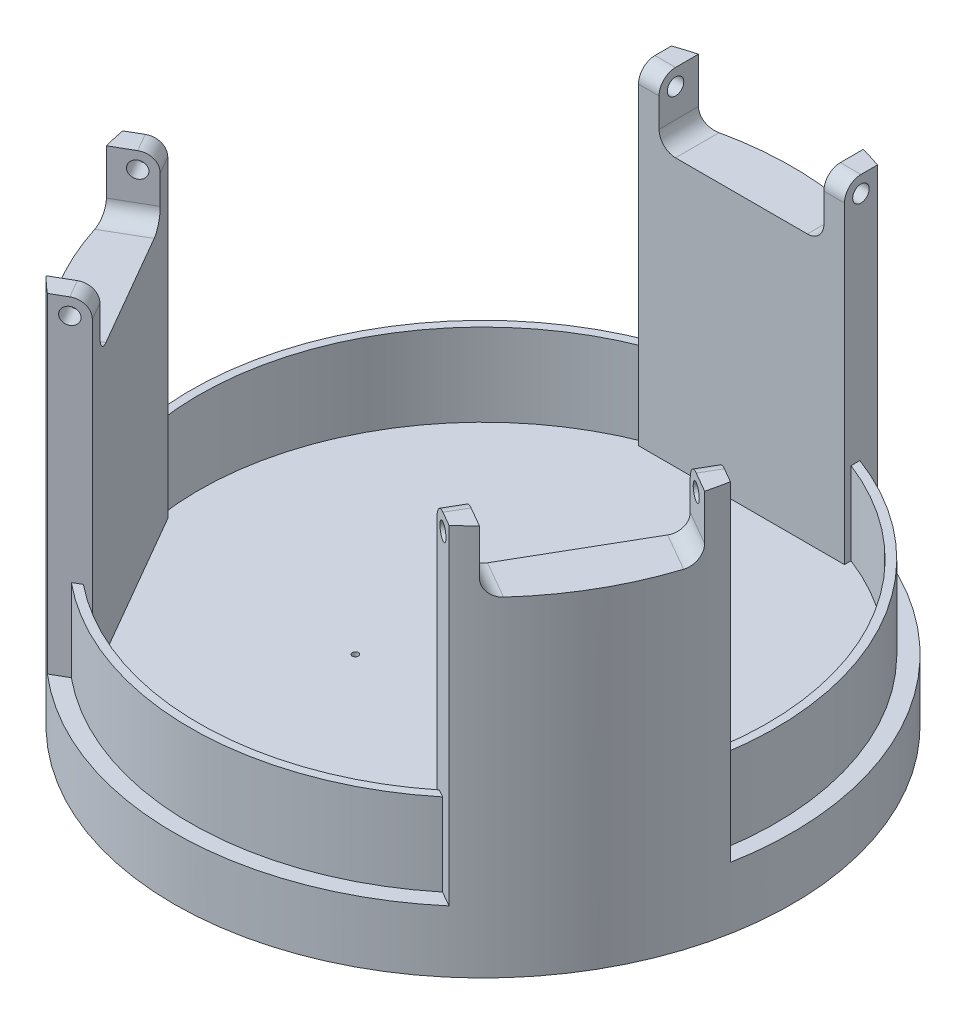
SolidWorks part; units mm, degrees
ref_plane "Front Plane" through (0, 0, 0) normal (0, 0, 1) x (1, 0, 0)
ref_plane "Top Plane" through (0, 0, 0) normal (0, 1, 0) x (1, 0, 0)
ref_plane "Right Plane" through (0, 0, 0) normal (1, 0, 0) x (0, 0, -1)
sketch "Sketch1" plane through (0, 0, 0) normal (0, 1, 0) x (1, 0, 0)
  circle A0 centre (0, 0) radius 75
  dimension "D1" = 150
extrude "Boss-Extrude1" add sketch "Sketch1" along normal blind 15
sketch "Sketch2" plane through (0, 15, 0) normal (0, 1, 0) x (1, 0, 0)
  line L2 (-25, 70.7107) -> (-25, 62.7107)
  line L3 (-25, 62.7107) -> (25, 62.7107)
  line L4 (25, 70.7107) -> (25, 62.7107)
  circle A0 centre (0, 0) radius 75 construction
  arc A1 (-25, 70.7107) -> (25, 70.7107) centre (0, 0) cw
  point P7 (0, 62.7107)
  dimension "D1" = 50
  dimension "D2" = 50
  dimension "D3" = 8
extrude "Boss-Extrude2" add sketch "Sketch2" along normal blind 80
sketch "Sketch3" plane through (0, 95, 0) normal (0, 1, 0) x (1, 0, 0)
  line L0 (-25, 62.7107) -> (25, 62.7107) construction
  line L2 (-20, 72.2842) -> (-20, 62.7107)
  line L3 (-20, 62.7107) -> (20, 62.7107)
  line L4 (20, 72.2842) -> (20, 62.7107)
  arc A0 (25, 70.7107) -> (-25, 70.7107) centre (0, 0) ccw construction
  arc A1 (-20, 72.2842) -> (20, 72.2842) centre (0, 0) cw
  point P11 (0, 62.7107)
  dimension "D1" = 40
extrude "Cut-Extrude1" cut sketch "Sketch3" against normal blind 15
hole_wizard "Ø4.0 mm Dowel Holes1" positions "Sketch4" profile "Sketch5" hole size "Ø4.0" standard "ISO" end condition through all
sketch "Sketch4" plane through (25, 0, 0) normal (1, 0, 0) x (0, 0, -1)
  line L0 (62.7107, 95) -> (62.7107, 15) construction
  line L1 (62.7107, 95) -> (70.7107, 95) construction
  point P0 (66.7107, 91)
  dimension "D1" = 4
  dimension "D2" = 4
sketch "Sketch5" plane through (25, 91, -66.7107) normal (0, 1, 0) x (0, 0, -1)
  line L0 (0, 0) -> (0, 100)
  line L1 (0, 100) -> (2, 100)
  line L2 (2, 100) -> (2, 0)
  line L5 (2, 0) -> (0, 0)
  line L11 (0, -6.35) -> (0, 107.95) construction
  dimension "Thru Hole Dia." = 4
  dimension "Thru Hole Depth" = 100
fillet "Fillet1" radius 4 2 edges at (-22.5, 95, -62.7107) (22.5, 95, -62.7107)
fillet "Fillet2" radius 4 2 edges at (-20, 80, -67.4974) (20, 80, -67.4974)
pattern_circular "CirPattern1" count 3 over 360 about axis through (0, 0, 0) along (0, 1, 0) of "Boss-Extrude2", "Cut-Extrude1", "Ø4.0 mm Dowel Holes1", "Fillet1", "Fillet2"
hole_wizard "Fori Alesato Ø1.5mm2" positions "Schizzo6" profile "Schizzo7" hole size "Ø1.5" standard "ISO" end condition through all
sketch "Schizzo6" plane through (0, 0, 0) normal (0, -1, 0) x (-1, 0, 0)
  line L1 (-15.4998, 15.4998) -> (15.4998, 15.4998)
  line L2 (-15.4998, 15.4998) -> (-15.4998, -15.4998)
  line L3 (-15.4998, -15.4998) -> (15.4998, -15.4998)
  line L4 (15.4998, 15.4998) -> (15.4998, -15.4998)
  point P0 (-15.4998, 15.4998)
  point P1 (15.4998, -15.4998)
  point P4 (-15.4998, -15.4998)
  point P5 (15.4998, 15.4998)
  point P23 (0, 15.4998)
  point P25 (15.4998, 0)
  dimension "D1" = 21.92
sketch "Schizzo7" plane through (15.4998, 0, -15.4998) normal (1, 0, 0) x (0, 0, -1)
  line L0 (0, 0) -> (0, 95)
  line L1 (0, 95) -> (0.75, 95)
  line L2 (0.75, 95) -> (0.75, 0)
  line L5 (0.75, 0) -> (0, 0)
  line L11 (0, -6.35) -> (0, 107.95) construction
  dimension "Thru Hole Dia." = 1.5
  dimension "Thru Hole Depth" = 95
sketch "Schizzo8" plane through (0, 15, 0) normal (0, 1, 0) x (1, 0, 0)
  circle A0 centre (0, 0) radius 70
  arc A1 (16, 73.2735) -> (-16, 73.2735) centre (0, 0) ccw construction
  dimension "D1" = 5
extrude "Estrusione-Sottile1" add sketch "Schizzo8" along normal blind 20 thin thin type mid plane wall 2
